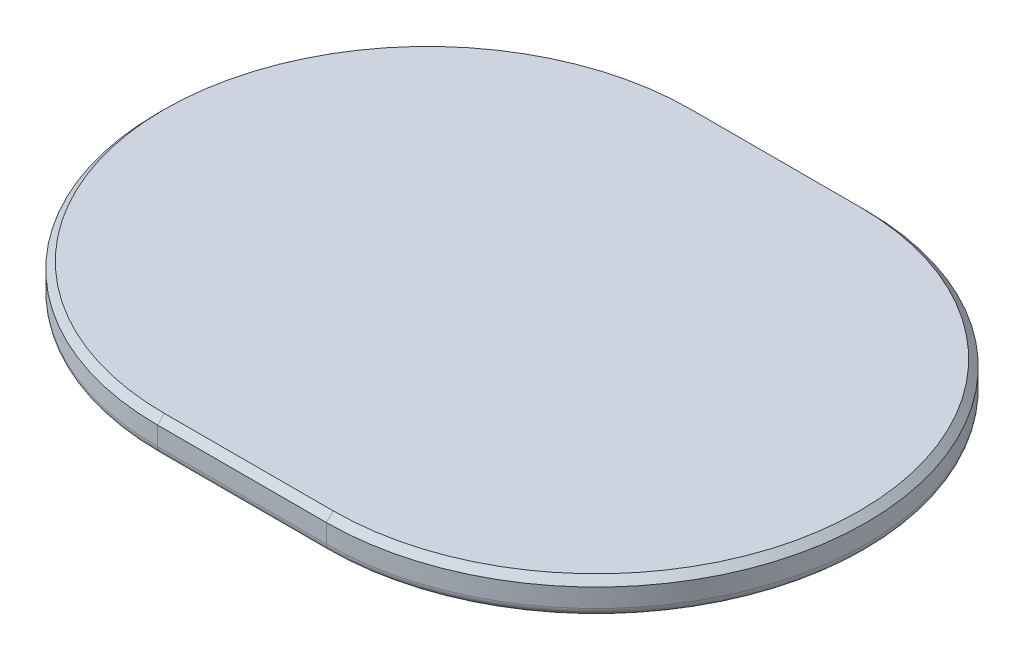
SolidWorks part; units mm, degrees
ref_plane "Front Plane" through (0, 0, 0) normal (0, 0, 1) x (1, 0, 0)
ref_plane "Top Plane" through (0, 0, 0) normal (0, 1, 0) x (1, 0, 0)
ref_plane "Right Plane" through (0, 0, 0) normal (1, 0, 0) x (0, 0, -1)
sketch "Sketch1" plane through (0, 0, 0) normal (0, 1, 0) x (1, 0, 0)
  line L0 (-10, 0) -> (10, 0) construction
  line L1 (-10, 32) -> (10, 32)
  line L2 (-10, -32) -> (10, -32)
  arc A0 (-10, 32) -> (-10, -32) centre (-10, 0) ccw
  arc A1 (10, -32) -> (10, 32) centre (10, 0) ccw
  point P2 (0, 0)
  dimension "D1" = 64
  dimension "D2" = 20
extrude "Boss-Extrude1" add sketch "Sketch1" along normal blind 4
chamfer "Chamfer1" distance 0.8 angle 45 4 edges at (0, 4, -32) (42, 4, 0) (0, 4, 32) (-42, 4, 0)
fillet "Fillet1" radius 1 4 edges at (0, 0, 32) (42, 0, 0) (0, 0, -32) (-42, 0, 0)
